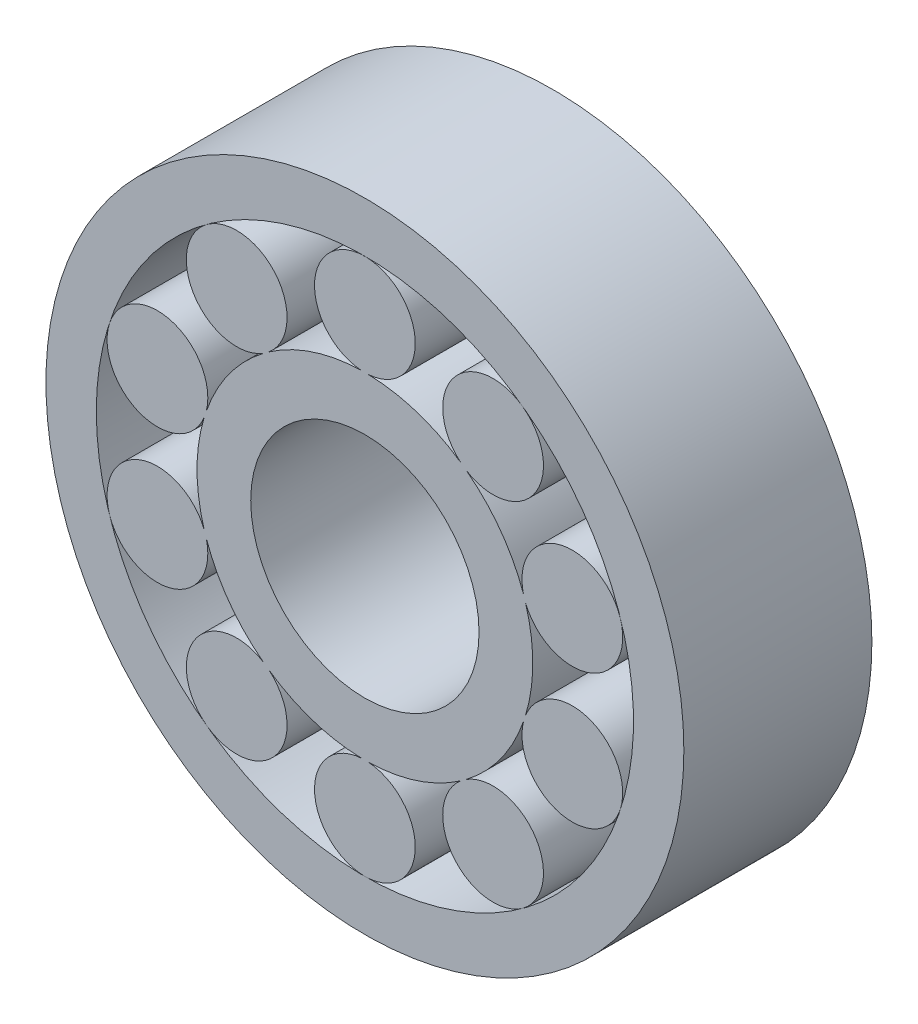
SolidWorks part; units mm, degrees
ref_plane "Alzado" through (0, 0, 0) normal (0, 0, 1) x (1, 0, 0)
ref_plane "Planta" through (0, 0, 0) normal (0, 1, 0) x (1, 0, 0)
ref_plane "Vista lateral" through (0, 0, 0) normal (1, 0, 0) x (0, 0, -1)
sketch "Croquis1" plane through (0, 0, 0) normal (0, 0, 1) x (1, 0, 0)
  circle A0 centre (0, 0) radius 23.75
  circle A1 centre (0, 0) radius 8.5
  dimension "D1" = 47.5
  dimension "D2" = 17
extrude "Saliente-Extruir1" add sketch "Croquis1" along normal blind 14
sketch "Croquis2" plane through (0, 0, 0) normal (0, 0, -1) x (-1, 0, 0)
  line L0 (0, 20) -> (0, 12.5) construction
  circle A0 centre (0, 0) radius 12.5
  circle A1 centre (0, 0) radius 20
  dimension "D1" = 25
  dimension "D2" = 40
extrude "Cortar-Extruir1" cut sketch "Croquis2" against normal blind 14
sketch "Croquis3" plane through (0, 0, 0) normal (0, 0, -1) x (-1, 0, 0)
  circle A2 centre (0, 16.24) radius 3.75
  circle A3 centre (0, 0) radius 20 construction
  circle A4 centre (9.5456, 13.1384) radius 3.75
  circle A5 centre (15.4452, 5.0184) radius 3.75
  circle A6 centre (15.4452, -5.0184) radius 3.75
  circle A7 centre (9.5456, -13.1384) radius 3.75
  circle A8 centre (0, -16.24) radius 3.75
  circle A9 centre (-9.5456, -13.1384) radius 3.75
  circle A10 centre (-15.4452, -5.0184) radius 3.75
  circle A11 centre (-15.4452, 5.0184) radius 3.75
  circle A12 centre (-9.5456, 13.1384) radius 3.75
  point P24 (0, 0)
  dimension "D1" = 7.5
  dimension "D2" = 16.24
  dimension "D3" = 10
extrude "Saliente-Extruir2" add sketch "Croquis3" against normal blind 14
